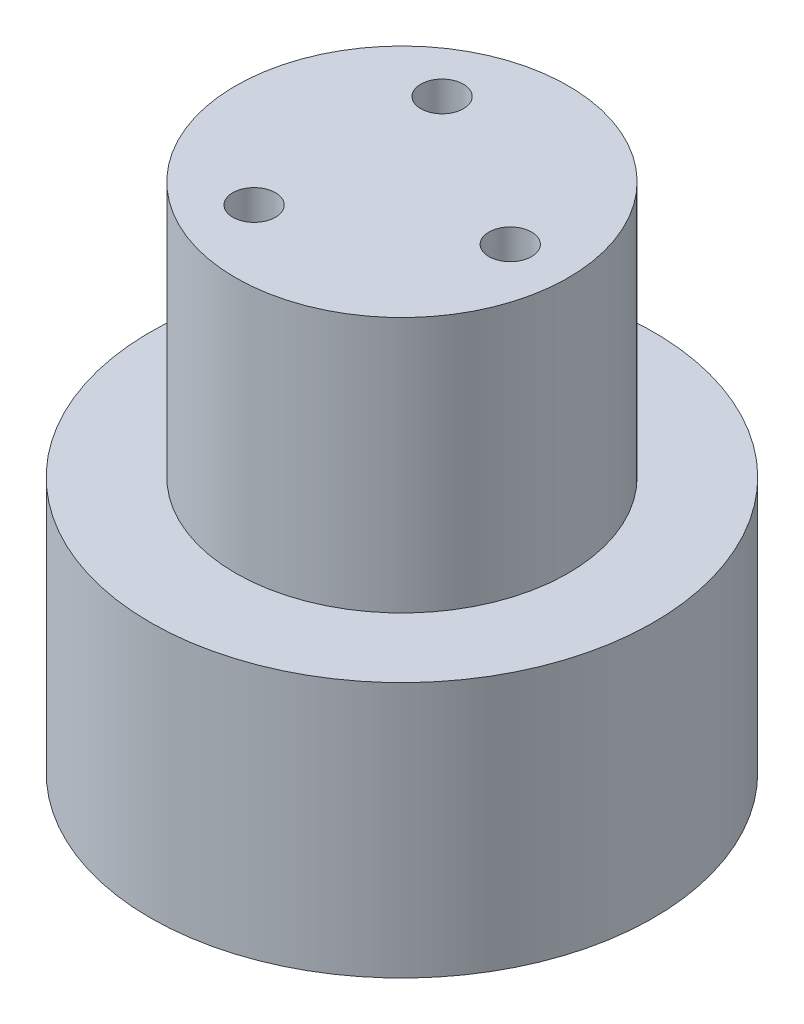
SolidWorks part; units mm, degrees
ref_plane "Спереди" through (0, 0, 0) normal (0, 0, 1) x (1, 0, 0)
ref_plane "Сверху" through (0, 0, 0) normal (0, 1, 0) x (1, 0, 0)
ref_plane "Справа" through (0, 0, 0) normal (1, 0, 0) x (0, 0, -1)
sketch "Эскиз1" plane through (0, 0, 0) normal (0, 1, 0) x (1, 0, 0)
  circle A0 centre (0, 0) radius 2.95
extrude "Бобышка-Вытянуть1" add sketch "Эскиз1" against normal blind 3
sketch "Эскиз2" plane through (0, 0, 0) normal (0, 1, 0) x (1, 0, 0)
  circle A0 centre (0, 0) radius 1.95
extrude "Бобышка-Вытянуть2" add sketch "Эскиз2" along normal blind 3 contours A0
sketch "Эскиз3" plane through (0, -3, 0) normal (0, -1, 0) x (1, 0, 0)
  circle A0 centre (1.27, 0) radius 0.25
  circle A1 centre (-0.631, 1.1022) radius 0.25
  circle A2 centre (-0.631, -1.1022) radius 0.25
extrude "Вырез-Вытянуть1" cut sketch "Эскиз3" against normal blind 6
